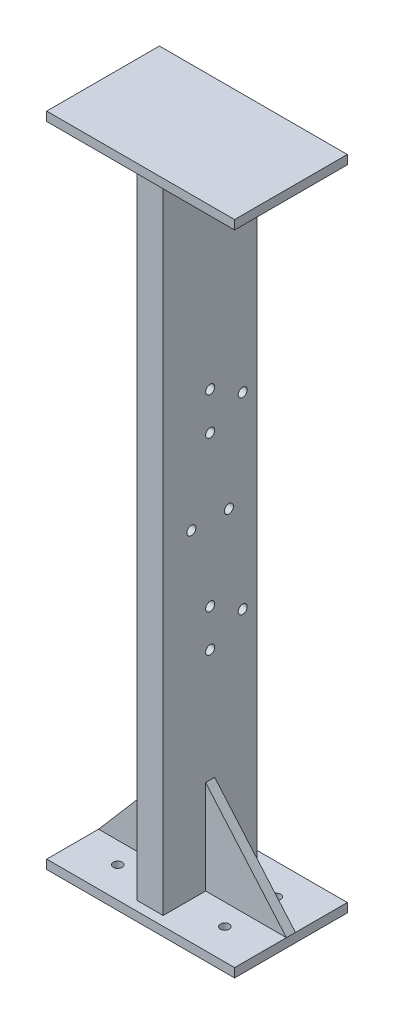
SolidWorks part; units mm, degrees
ref_plane "Front Plane" through (0, 0, 0) normal (0, 0, 1) x (1, 0, 0)
ref_plane "Top Plane" through (0, 0, 0) normal (0, 1, 0) x (1, 0, 0)
ref_plane "Right Plane" through (0, 0, 0) normal (1, 0, 0) x (0, 0, -1)
sketch "Sketch2" plane through (0, 0, 0) normal (0, 1, 0) x (1, 0, 0)
  line L0 (12, 12) -> (12, 113)
  line L1 (0, 0) -> (35, 0)
  line L2 (0, 0) -> (0, 125)
  line L3 (0, 125) -> (35, 125)
  line L4 (35, 0) -> (35, 125)
  line L5 (12, 113) -> (23, 113)
  line L6 (23, 12) -> (23, 113)
  line L7 (12, 12) -> (23, 12)
  dimension "D1" = 125
  dimension "D2" = 35
  dimension "D3" = 12
extrude "Boss-Extrude1" add sketch "Sketch2" along normal blind 850
sketch "Sketch3" plane through (35, 0, 0) normal (1, 0, 0) x (0, 0, -1)
  line L0 (62.5, 850) -> (62.5, 0) construction
  line L1 (0, 850) -> (125, 850) construction
  line L2 (0, 0) -> (125, 0) construction
  line L3 (37.5, 425) -> (87.5, 425) construction
  circle A0 centre (62.5, 575) radius 6
  circle A1 centre (62.5, 525) radius 6
  circle A2 centre (105.8013, 550) radius 6
  circle A3 centre (37.5, 425) radius 6
  circle A4 centre (87.5, 425) radius 6
  circle A8 centre (105.8013, 300) radius 6
  circle A9 centre (62.5, 325) radius 6
  circle A10 centre (62.5, 275) radius 6
  point P23 (62.5, 425)
  point P24 (62.5, 425)
  dimension "D1" = 12
  dimension "D6" = 150
  dimension "D2" = 50
  dimension "D3" = 50
  dimension "D4" = 50
  dimension "D5" = 50
extrude "Cut-Extrude1" cut sketch "Sketch3" against normal through all
sketch "Sketch4" plane through (0, 0, 0) normal (0, -1, 0) x (-1, 0, 0)
  line L0 (-35, 0) -> (0, 125) construction
  line L2 (107.5, -12.5) -> (-142.5, -12.5)
  line L3 (107.5, -12.5) -> (107.5, 137.5)
  line L4 (107.5, 137.5) -> (-142.5, 137.5)
  line L5 (-142.5, -12.5) -> (-142.5, 137.5)
  line L6 (107.5, -12.5) -> (-142.5, 137.5) construction
  line L7 (107.5, 137.5) -> (-142.5, -12.5) construction
  point P4 (-17.5, 62.5)
  dimension "D1" = 250
  dimension "D2" = 150
extrude "Boss-Extrude2" add sketch "Sketch4" along normal blind 12
sketch "Sketch5" plane through (0, 850, 0) normal (0, 1, 0) x (1, 0, 0)
  line L0 (0, 125) -> (35, 0) construction
  line L2 (-107.5, -12.5) -> (142.5, -12.5)
  line L3 (-107.5, -12.5) -> (-107.5, 137.5)
  line L4 (-107.5, 137.5) -> (142.5, 137.5)
  line L5 (142.5, -12.5) -> (142.5, 137.5)
  line L6 (-107.5, -12.5) -> (142.5, 137.5) construction
  line L7 (-107.5, 137.5) -> (142.5, -12.5) construction
  point P4 (17.5, 62.5)
extrude "Boss-Extrude3" add sketch "Sketch5" along normal blind 12
sketch "Sketch7" plane through (0, 0, -125) normal (0, 0, -1) x (-1, 0, 0)
  line L0 (-35, 0) -> (-35, 125)
  line L1 (-35, 850) -> (-35, 0) construction
  line L2 (-35, 125) -> (-142.5, 0)
  line L3 (-142.5, 0) -> (-35, 0)
  line L4 (-17.5, 0) -> (-17.5, 850) construction
  line L5 (-35, 0) -> (0, 0) construction
  line L6 (-35, 850) -> (0, 850) construction
  line L7 (0, 125) -> (107.5, 0)
  line L8 (0, 0) -> (0, 125)
  line L9 (107.5, 0) -> (0, 0)
  dimension "D1" = 125
extrude "Boss-Extrude4" add sketch "Sketch7" along normal mid plane 12 from offset 62.5 offset against normal yes
sketch "Sketch8" plane through (0, 0, 0) normal (0, 1, 0) x (1, 0, 0)
  line L0 (0, 0) -> (0, 56.5) construction
  line L1 (0, 28.25) -> (-107.5, 28.25) construction
  line L2 (-107.5, -12.5) -> (-107.5, 56.5) construction
  line L3 (35, 28.25) -> (142.5, 28.25) construction
  line L4 (35, 0) -> (35, 56.5) construction
  line L5 (142.5, 56.5) -> (142.5, -12.5) construction
  line L9 (0, 68.5) -> (0, 125) construction
  line L10 (0, 96.75) -> (-107.5, 96.75) construction
  line L11 (-107.5, 68.5) -> (-107.5, 137.5) construction
  circle A0 centre (-53.75, 28.25) radius 6
  circle A1 centre (-53.75, 96.75) radius 6
  circle A2 centre (88.75, 28.25) radius 6
  circle A3 centre (88.75, 96.75) radius 6
  dimension "D1" = 12
extrude "Cut-Extrude2" cut sketch "Sketch8" against normal up to surface (12 mm away) up to face at (17.5, -12, -62.5)
equation "\"mbtOD\" = 500"
equation "\"mbtT\" = 6"
equation "\"mbtL\" = 3000"
equation "\"mbtFlangeOD\" = 650"
equation "\"mbtFlangeT\" = 12"
equation "\"mbtFlangeBoltCircleDia\" = 650"
equation "\"mbtFlangeHoleDia\" = 12"
equation "\"mbtOringSize\" = 10 "
equation "\"mbtOringDia\" = 620"
equation "\"mbtWidth\" = 2250"
equation "\"skiWidth\" = 1250"
equation "\"D1@Boss-Extrude1\"=\"mbtFlangeOD\"+200mm"
equation "\"D1@Boss-Extrude2\"=\"mbtFlangeT\""
